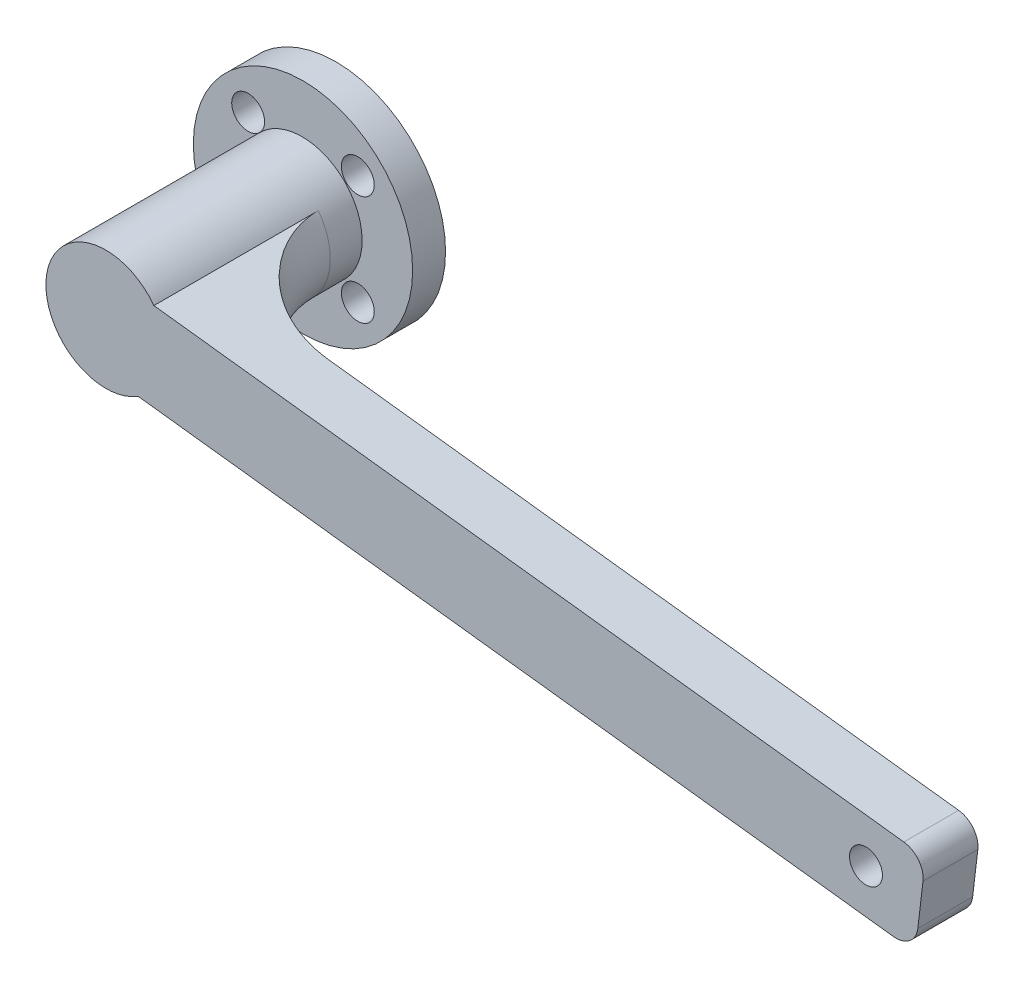
SolidWorks part; units mm, degrees
ref_plane "前视基准面" through (0, 0, 0) normal (0, 0, 1) x (1, 0, 0)
ref_plane "上视基准面" through (0, 0, 0) normal (0, 1, 0) x (1, 0, 0)
ref_plane "右视基准面" through (0, 0, 0) normal (1, 0, 0) x (0, 0, -1)
sketch "草图1" plane through (0, 0, 0) normal (0, 0, 1) x (1, 0, 0)
  circle A0 centre (0, 0) radius 10
  dimension "D1" = 20
extrude "凸台-拉伸1" add sketch "草图1" along normal blind 3
sketch "草图2" plane through (0, 0, 3) normal (0, 0, 1) x (1, 0, 0)
  line L1 (5, -5) -> (-5, -5)
  line L2 (5, -5) -> (5, 5)
  line L3 (5, 5) -> (-5, 5)
  line L4 (-5, -5) -> (-5, 5)
  line L5 (5, -5) -> (-5, 5) construction
  line L6 (5, 5) -> (-5, -5) construction
  circle A0 centre (0, 0) radius 1.5
  circle A2 centre (5, 5) radius 1.5
  circle A3 centre (-5, 5) radius 1.5
  circle A4 centre (-5, -5) radius 1.5
  circle A5 centre (5, -5) radius 1.5
  dimension "D1" = 3
  dimension "D2" = 10
  dimension "D4" = 3
  dimension "D3" = 10
extrude "切除-拉伸1" cut sketch "草图2" against normal through all contours L3 A3 L4 | L4 A3 L3 | L2 A2 L3 | L3 A2 L2 | L4 A4 L1 | L1 A4 L4 | L1 A5 L2 | L2 A5 L1 | A0
sketch "草图3" plane through (0, 0, 3) normal (0, 0, 1) x (1, 0, 0)
  circle A0 centre (-0.0744, 0.0744) radius 5.4659
  circle A1 centre (-5, 5) radius 1.5 construction
  circle A2 centre (0, 0) radius 10
  circle A3 centre (0, 0) radius 10
  circle A4 centre (-5, 5) radius 1.5
  circle M5 centre (0, 0) radius 1.5
  dimension "D1" = 0
extrude "凸台-拉伸2" add sketch "草图3" along normal blind 12.9 contours A0 M5
sketch "草图4" plane through (0, 0, 0) normal (0, 0, -1) x (-1, 0, 0)
  circle A0 centre (0, 0) radius 1.5 construction
  circle A3 centre (0, 0) radius 1.5
extrude "凸台-拉伸4" add sketch "草图4" against normal up to surface (15.9 mm away) up to face at (1.5, 0, 15.9)
sketch "草图5" plane through (0, 0, 15.9) normal (0, 0, 1) x (1, 0, 0)
  line L0 (-0.2722, -0.1379) -> (74.1987, -9.0309) construction
  line L1 (74.673, -5.0592) -> (73.7244, -13.0027)
  line L2 (73.7244, -13.0027) -> (-0.7465, -4.1097)
  line L3 (-0.7465, -4.1097) -> (0.2021, 3.8339)
  line L4 (74.673, -5.0592) -> (0.2021, 3.8339)
  dimension "D1" = 75
  dimension "D2" = 4
extrude "凸台-拉伸5" add sketch "草图5" along normal blind 5
sketch "草图6" plane through (0, 0, 20.9) normal (0, 0, 1) x (1, 0, 0)
  line L0 (74.1987, -9.0309) -> (69.2339, -8.4381) construction
  line L1 (73.7244, -13.0027) -> (74.673, -5.0592) construction
  circle A0 centre (69.2339, -8.4381) radius 1.5
  dimension "D1" = 3
  dimension "D2" = 5
extrude "切除-拉伸2" cut sketch "草图6" against normal through all
sketch "草图7" plane through (0, 0, 15.9) normal (0, 0, 1) x (1, 0, 0)
  line L3 (0.2021, 3.8339) -> (4.3059, 3.3438)
  line L4 (2.8557, -4.5398) -> (-0.7465, -4.1097)
  line L5 (-0.7465, -4.1097) -> (0.2021, 3.8339)
  line L6 (0.2021, 3.8339) -> (4.3059, 3.3438)
  line L7 (2.8557, -4.5398) -> (-0.7465, -4.1097)
  line L8 (-0.7465, -4.1097) -> (0.2021, 3.8339)
  arc A1 (4.3059, 3.3438) -> (2.8557, -4.5398) centre (-0.0744, 0.0744) ccw
  arc A2 (4.3059, 3.3438) -> (2.8557, -4.5398) centre (-0.0744, 0.0744) ccw
  dimension "D1" = 0
extrude "凸台-拉伸8" add sketch "草图7" along normal blind 5 contours L6 A2 L7 L8
fillet "圆角1" radius 10 1 edges at (5.3013, -0.9145, 15.9)
fillet "圆角2" radius 2 2 edges at (73.7244, -13.0027, 18.4) (74.673, -5.0592, 18.4)
